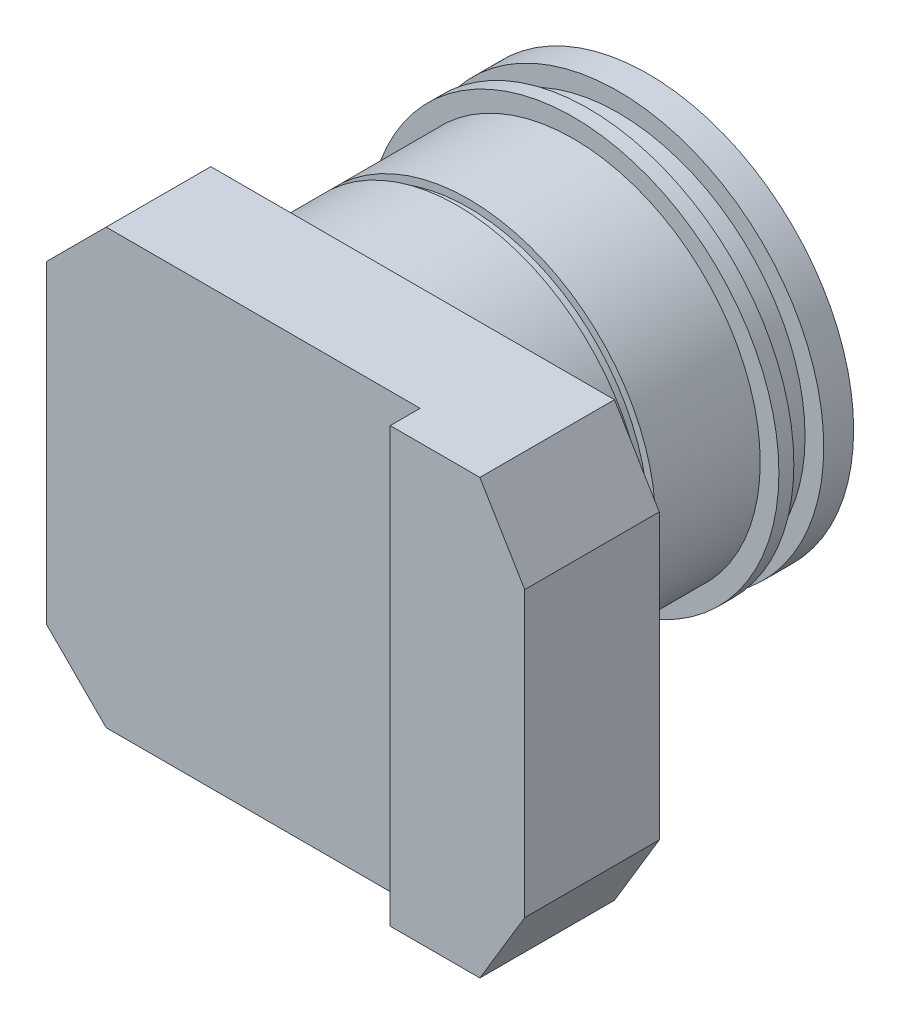
SolidWorks part; units mm, degrees
ref_plane "Front Plane" through (0, 0, 0) normal (0, 0, 1) x (1, 0, 0)
ref_plane "Top Plane" through (0, 0, 0) normal (0, 1, 0) x (1, 0, 0)
ref_plane "Right Plane" through (0, 0, 0) normal (1, 0, 0) x (0, 0, -1)
sketch "Sketch1" plane through (0, 0, 0) normal (0, 0, 1) x (1, 0, 0)
  line L1 (-17, 14.5) -> (17, 14.5)
  line L2 (-17, 14.5) -> (-17, -14.5)
  line L3 (-17, -14.5) -> (17, -14.5)
  line L4 (17, 14.5) -> (17, -14.5)
  line L5 (-17, 14.5) -> (17, -14.5) construction
  line L6 (-17, -14.5) -> (17, 14.5) construction
  point P0 (0, 0)
  dimension "D1" = 34
  dimension "D2" = 29
extrude "Boss-Extrude1" add sketch "Sketch1" along normal mid plane 7 contours L2 L3 L4 L1
sketch "Sketch2" plane through (0, 0, 3.5) normal (0, 0, 1) x (1, 0, 0)
  line L0 (-17, -14.5) -> (17, -14.5) construction
  line L1 (17, 14.5) -> (8, 14.5)
  line L2 (17, 14.5) -> (17, -14.5)
  line L3 (17, -14.5) -> (8, -14.5)
  line L4 (8, 14.5) -> (8, -14.5)
  dimension "D1" = 9
extrude "Boss-Extrude2" add sketch "Sketch2" along normal blind 2
sketch "Sketch3" plane through (0, 0, -3.5) normal (0, 0, -1) x (-1, 0, 0)
  line L0 (-14, -14.5) -> (-17, -9.5)
  line L1 (17, -14.5) -> (-17, -14.5) construction
  line L2 (-17, 14.5) -> (-17, -14.5) construction
  line L3 (-17, -9.5) -> (-17, -14.5)
  line L4 (-17, -14.5) -> (-14, -14.5)
  line L5 (13, -14.5) -> (17, -10.5)
  line L6 (17, 14.5) -> (17, -14.5) construction
  line L7 (17, -10.5) -> (17, -14.5)
  line L8 (17, -14.5) -> (13, -14.5)
  line L9 (17, 10.5) -> (13, 14.5)
  line L10 (17, 14.5) -> (-17, 14.5) construction
  line L11 (13, 14.5) -> (17, 14.5)
  line L12 (17, 14.5) -> (17, 10.5)
  line L13 (-17, 9.5) -> (-14, 14.5)
  line L14 (-14, 14.5) -> (-17, 14.5)
  line L15 (-17, 14.5) -> (-17, 9.5)
  dimension "D1" = 3
  dimension "D2" = 5
  dimension "D3" = 4
  dimension "D4" = 4
  dimension "D5" = 4
  dimension "D6" = 4
extrude "Cut-Extrude1" cut sketch "Sketch3" against normal through all
sketch "Sketch4" plane through (0, 0, 0) normal (0, 1, 0) x (1, 0, 0)
  line L0 (-17, 3.5) -> (-4.5, 3.5)
  line L1 (-17, 3.5) -> (-17, 11.5)
  line L2 (-17, 11.5) -> (-16.5, 11.5)
  line L3 (-16.5, 11.5) -> (-16.5, 12.25)
  line L4 (-16.5, 12.25) -> (-17, 12.25)
  line L5 (-17, 12.25) -> (-17, 19.25)
  line L6 (-17, 19.25) -> (-18.25, 19.25)
  line L7 (-18.25, 19.25) -> (-18.25, 20.25)
  line L8 (-18.25, 20.25) -> (-17, 20.25)
  line L9 (-17, 20.25) -> (-17, 22.25)
  line L10 (-17, 22.25) -> (-18.25, 22.25)
  line L11 (-18.25, 22.25) -> (-18.25, 24.25)
  line L12 (-18.25, 24.25) -> (-4.5, 24.25)
  line L13 (-17, 3.5) -> (8, 3.5) construction
  line L14 (-13, -3.5) -> (8, -3.5) construction
  line L15 (-4.5, 24.25) -> (-4.5, 3.5) construction
  line L16 (-4.5, 3.5) -> (-4.5, 24.25)
  dimension "D1" = 8
  dimension "D2" = 27.75
  dimension "D3" = 2
  dimension "D4" = 1
  dimension "D5" = 2
  dimension "D6" = 7
  dimension "D7" = 13.75
  dimension "D8" = 0.5
revolve "Revolve1" add sketch "Sketch4" angle 360 about L16
sketch "Sketch5" plane through (0, 0, -24.25) normal (0, 0, -1) x (-1, 0, 0)
  circle A0 centre (4.5, 0) radius 9.75
  circle A2 centre (4.5, 0) radius 13.75 construction
  dimension "D1" = 4
extrude "Cut-Extrude2" cut sketch "Sketch5" against normal blind 5 draft 45
sketch "Sketch6" plane through (0, 0, 0) normal (0, 1, 0) x (1, 0, 0)
  line L0 (-9.25, 19.25) -> (-4.5, 19.25)
  line L1 (-4.5, 19.25) -> (-4.5, 24)
  line L2 (0.25, 19.25) -> (-9.25, 19.25) construction
  line L3 (-14.25, 24.25) -> (-9.25, 19.25) construction
  line L4 (-9.25, 19.25) -> (0.25, 19.25) construction
  line L5 (0.25, 19.25) -> (5.25, 24.25) construction
  arc A0 (-9.25, 19.25) -> (-4.5, 24) centre (-4.5, 19.25) cw
revolve "Revolve2" add sketch "Sketch6" angle 360 about L1
